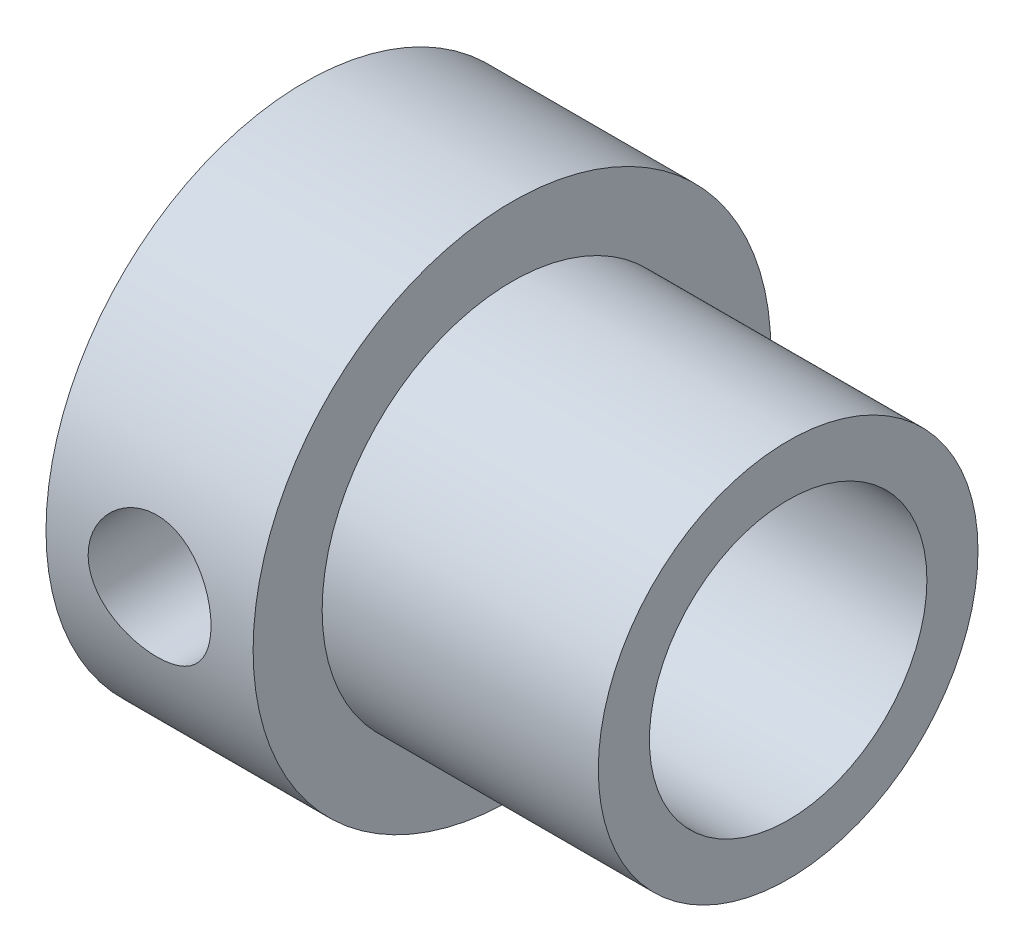
SolidWorks part; units mm, degrees
ref_plane "Front Plane" through (0, 0, 0) normal (0, 0, 1) x (1, 0, 0)
ref_plane "Top Plane" through (0, 0, 0) normal (0, 1, 0) x (1, 0, 0)
ref_plane "Right Plane" through (0, 0, 0) normal (1, 0, 0) x (0, 0, -1)
sketch "Sketch1" plane through (0, 0, 0) normal (1, 0, 0) x (0, 0, -1)
  circle A0 centre (0, 0) radius 4.7625
  circle A1 centre (0, 0) radius 2.5527
  dimension "D1" = 5.1054
  dimension "D2" = 9.525
extrude "Boss-Extrude1" add sketch "Sketch1" along normal blind 8.89
sketch "Sketch2" plane through (0, 0, 0) normal (0, 0, 1) x (1, 0, 0)
  line L0 (8.89, 4.7625) -> (0, 4.7625) construction
  line L1 (3.81, 4.7625) -> (8.89, 4.7625)
  line L2 (3.81, 4.7625) -> (3.81, 3.4925)
  line L3 (3.81, 3.4925) -> (8.89, 3.4925)
  line L4 (8.89, 4.7625) -> (8.89, 3.4925)
  line L5 (0, 4.7625) -> (0, -4.7625) construction
  line L7 (8.89, -4.7625) -> (8.89, 4.7625) construction
  dimension "D1" = 3.81
  dimension "D2" = 0
  dimension "D3" = 1.27
ref_axis "Axis1" through (8.89, 0, 0) along (-1, 0, 0)
revolve "Cut-Revolve1" cut sketch "Sketch2" angle 360 about axis through (8.89, 0, 0) along (-1, 0, 0)
sketch "Sketch7" plane through (0, 0, 0) normal (0, 1, 0) x (1, 0, 0)
  line L0 (8.89, 0) -> (0, 0) construction
  line L1 (0, 4.7625) -> (0, -4.7625) construction
  circle A0 centre (1.905, 3.81) radius 0.3969
  dimension "D1" = 0.7937
  dimension "D2" = 3.81
  dimension "D3" = 1.905
extrude "Cut-Extrude1" cut sketch "Sketch7" against normal through all and the other way through all
hole_wizard "ShaftSetScrew" positions "Sketch4" profile "Sketch3" tap size "#4-40" standard "ANSI Inch"
sketch "Sketch4" plane through (0, 0, 0) normal (0, 0, 1) x (1, 0, 0)
  line L0 (8.89, 0) -> (0, 0) construction
  line L1 (0, 4.7625) -> (0, -4.7625) construction
  point P0 (1.905, 0)
  dimension "D1" = 1.905
sketch "Sketch3" plane through (1.905, 0, 0) normal (1, 0, 0) x (0, 1, 0)
  line L0 (0, 0) -> (0, 4.7625)
  line L1 (0, 4.7625) -> (1.1303, 4.7625)
  line L2 (1.1303, 4.7625) -> (1.1303, 0)
  line L5 (1.1303, 0) -> (0, 0)
  line L11 (0, -6.35) -> (0, 107.95) construction
  dimension "Thread Major Dia." = 2.2606
  dimension "Thru Tap Drill Depth" = 4.7625
